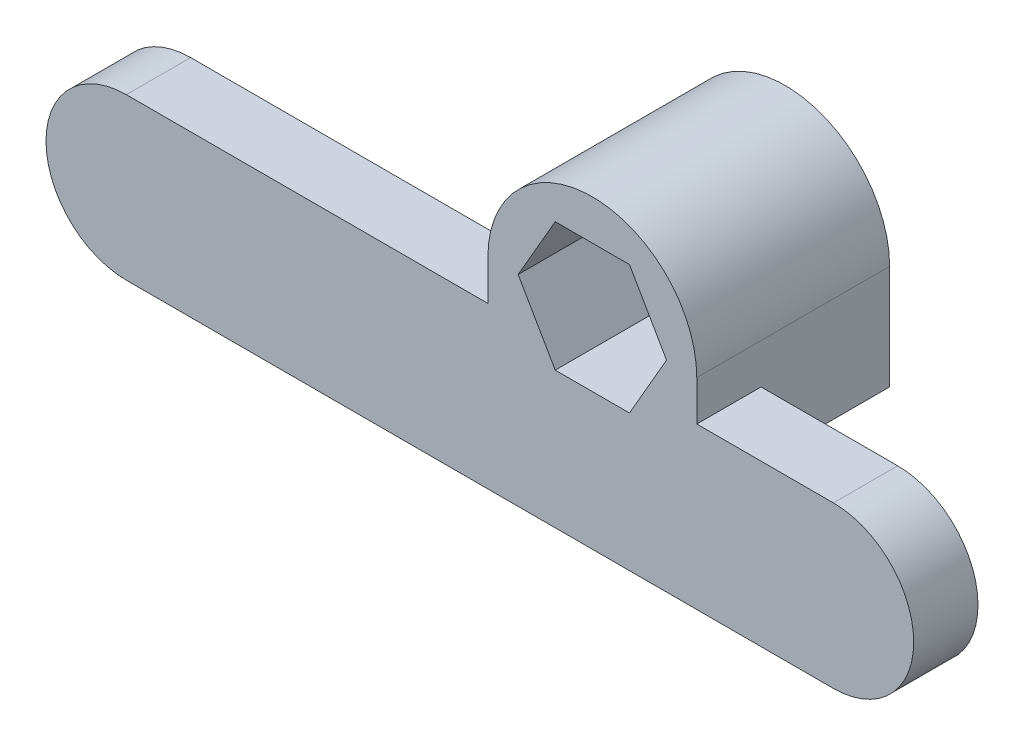
SolidWorks part; units mm, degrees
ref_plane "Front Plane" through (0, 0, 0) normal (0, 0, 1) x (1, 0, 0)
ref_plane "Top Plane" through (0, 0, 0) normal (0, 1, 0) x (1, 0, 0)
ref_plane "Right Plane" through (0, 0, 0) normal (1, 0, 0) x (0, 0, -1)
sketch "Sketch1" plane through (0, 0, 0) normal (0, 0, 1) x (1, 0, 0)
  line L0 (-14.5, -3.75) -> (7.5, -3.75) construction
  line L1 (-14.5, -1.25) -> (-3.25, -1.25)
  line L2 (-14.5, -6.25) -> (7.5, -6.25)
  line L4 (3.25, -1.25) -> (7.5, -1.25)
  line L6 (-3.25, 0) -> (-3.25, -1.25)
  line L8 (3.25, 0) -> (3.25, -1.25)
  circle A0 centre (0, 0) radius 1.25
  arc A1 (3.25, 0) -> (-3.25, 0) centre (0, 0) ccw
  arc A2 (-14.5, -1.25) -> (-14.5, -6.25) centre (-14.5, -3.75) ccw
  arc A3 (7.5, -6.25) -> (7.5, -1.25) centre (7.5, -3.75) ccw
  circle A4 centre (0, 0) radius 3.25 construction
  point P7 (7.5, -3.75)
  dimension "D2" = 2.5
  dimension "D4" = 2.5
  dimension "D3" = 22
  dimension "D5" = 7.5
  dimension "D1" = 2
extrude "Boss-Extrude1" add sketch "Sketch1" along normal blind 2
sketch "Sketch2" plane through (0, 0, 2) normal (0, 0, 1) x (1, 0, 0)
  line L0 (-3.25, -1.25) -> (-14.5, -1.25) construction
  line L1 (-10, -1.25) -> (-15, -1.25)
  line L2 (-10, -1.25) -> (-10, -6.25)
  line L3 (-10, -6.25) -> (-15, -6.25)
  line L4 (-15, -1.25) -> (-15, -6.25)
  line L5 (-14.5, -6.25) -> (7.5, -6.25) construction
  line L6 (7.5, -1.25) -> (3.25, -1.25) construction
  line L7 (3, -1.25) -> (8, -1.25)
  line L8 (3, -1.25) -> (3, -6.25)
  line L9 (3, -6.25) -> (8, -6.25)
  line L10 (8, -1.25) -> (8, -6.25)
  line L11 (-15, -3.75) -> (-17, -3.75) construction
  line L12 (8, -3.75) -> (10, -3.75) construction
  line L14 (-3.25, 0) -> (3.25, 0)
  line L15 (-3.25, 0) -> (-3.25, -3.45)
  line L16 (-3.25, -1.25) -> (-14.5, -1.25)
  line L17 (-14.5, -6.25) -> (7.5, -6.25)
  line L18 (7.5, -1.25) -> (3.25, -1.25)
  line L19 (-3.25, -1.25) -> (-14.5, -1.25)
  line L20 (-14.5, -6.25) -> (7.5, -6.25)
  line L21 (7.5, -1.25) -> (3.25, -1.25)
  line L22 (-3.25, -3.45) -> (3.25, -3.45)
  line L23 (3.25, 0) -> (3.25, -3.45)
  line L24 (3.25, -1.25) -> (3.25, 0)
  line L25 (3.25, -1.25) -> (3.25, 0)
  line L26 (-3.25, 0) -> (-3.25, -1.25)
  line L27 (-3.25, 0) -> (-3.25, -1.25)
  line L28 (-8, -1.25) -> (-3, -1.25)
  line L29 (-8, -1.25) -> (-8, -6.25)
  line L30 (-8, -6.25) -> (-3, -6.25)
  line L31 (-3, -1.25) -> (-3, -6.25)
  arc A0 (-14.5, -1.25) -> (-14.5, -6.25) centre (-14.5, -3.75) ccw construction
  arc A1 (7.5, -6.25) -> (7.5, -1.25) centre (7.5, -3.75) ccw construction
  circle A2 centre (0, 0) radius 3.25
  circle A3 centre (0, 0) radius 3.45
  arc A5 (3.25, 0) -> (-3.25, 0) centre (0, 0) ccw
  arc A6 (-14.5, -1.25) -> (-14.5, -6.25) centre (-14.5, -3.75) ccw
  arc A7 (7.5, -6.25) -> (7.5, -1.25) centre (7.5, -3.75) ccw
  arc A8 (3.25, 0) -> (-3.25, 0) centre (0, 0) ccw
  arc A9 (-14.5, -1.25) -> (-14.5, -6.25) centre (-14.5, -3.75) ccw
  arc A10 (7.5, -6.25) -> (7.5, -1.25) centre (7.5, -3.75) ccw
  arc M20 (-14.5, -1.25) -> (-14.5, -6.25) centre (-14.5, -3.75) ccw
  line M21 (-14.5, -6.25) -> (7.5, -6.25)
  arc M22 (7.5, -6.25) -> (7.5, -1.25) centre (7.5, -3.75) ccw
  dimension "D1" = 5
  dimension "D2" = 5
  dimension "D5" = 5
  dimension "D3" = 0
  dimension "D4" = 0.2
extrude "Boss-Extrude2" add sketch "Sketch2" along normal blind 4 contours L4 M20 | A3 L2 L8 M21 | L10 M22
sketch "Sketch3" plane through (0, 0, 2) normal (0, 0, 1) x (1, 0, 0)
  line L0 (-3, -6.25) -> (3, -6.25) construction
  line L2 (-3.25, 0) -> (-3.25, -3.25)
  line L3 (-3.25, -3.25) -> (-1.05, -3.25)
  line L4 (3.25, 0) -> (3.25, -3.25)
  line L6 (-1.05, -3.25) -> (-1.05, -6.25)
  line L7 (-1.05, -6.25) -> (1.05, -6.25)
  line L8 (1.05, -3.25) -> (1.05, -6.25)
  line L9 (1.05, -3.25) -> (3.25, -3.25)
  arc A0 (3.25, 0) -> (-3.25, 0) centre (0, 0) ccw
  arc A1 (3.25, 0) -> (-3.25, 0) centre (0, 0) ccw construction
  circle A2 centre (0, 0) radius 1.25 construction
  circle A3 centre (0, 0) radius 1.25
  dimension "D1" = 2.2
  dimension "D2" = 2.2
extrude "Boss-Extrude3" add sketch "Sketch3" along normal blind 4 separate body
sketch "Sketch4" plane through (0, 0, 6) normal (0, 0, 1) x (1, 0, 0)
  line L3 (7.5, -1.25) -> (3.25, -1.25)
  line L4 (-14.5, -6.25) -> (7.5, -6.25)
  line L5 (-3.25, -1.25) -> (-14.5, -1.25)
  line L6 (7.5, -1.25) -> (3.25, -1.25)
  line L7 (-14.5, -6.25) -> (7.5, -6.25)
  line L8 (-3.25, -1.25) -> (-14.5, -1.25)
  line L11 (-3.25, 0) -> (-3.25, -1.25)
  line L12 (-3.25, 0) -> (-3.25, -1.25)
  line L13 (3.25, -1.25) -> (3.25, 0)
  line L14 (3.25, -1.25) -> (3.25, 0)
  arc A0 (8, -6.1995) -> (8, -1.3005) centre (7.5, -3.75) ccw construction
  arc A1 (8, -6.1995) -> (8, -1.3005) centre (7.5, -3.75) ccw
  circle A2 centre (0, 0) radius 1.25 construction
  circle A3 centre (0, 0) radius 1.25
  arc A7 (3.25, 0) -> (-3.25, 0) centre (0, 0) ccw
  arc A9 (7.5, -6.25) -> (7.5, -1.25) centre (7.5, -3.75) ccw
  arc A10 (-14.5, -1.25) -> (-14.5, -6.25) centre (-14.5, -3.75) ccw
  arc A12 (3.25, 0) -> (-3.25, 0) centre (0, 0) ccw
  arc A14 (7.5, -6.25) -> (7.5, -1.25) centre (7.5, -3.75) ccw
  arc A15 (-14.5, -1.25) -> (-14.5, -6.25) centre (-14.5, -3.75) ccw
  dimension "D1" = 0
delete or keep bodies "Body-Delete/Keep 1" type delete bodies bodies 102
extrude "Boss-Extrude4" add sketch "Sketch4" along normal blind 2
sketch "Sketch5" plane through (0, 0, 8) normal (0, 0, 1) x (1, 0, 0)
  line L1 (1.1547, 2) -> (-1.1547, 2)
  line L2 (-1.1547, 2) -> (-2.3094, 0)
  line L3 (-2.3094, 0) -> (-1.1547, -2)
  line L4 (-1.1547, -2) -> (1.1547, -2)
  line L5 (1.1547, -2) -> (2.3094, 0)
  line L6 (2.3094, 0) -> (1.1547, 2)
  circle A0 centre (0, 0) radius 2 construction
  dimension "D1" = 4
extrude "Cut-Extrude1" cut sketch "Sketch5" against normal offset from surface (4 mm away) 2 up to face at (0, -2.7813, 2)
